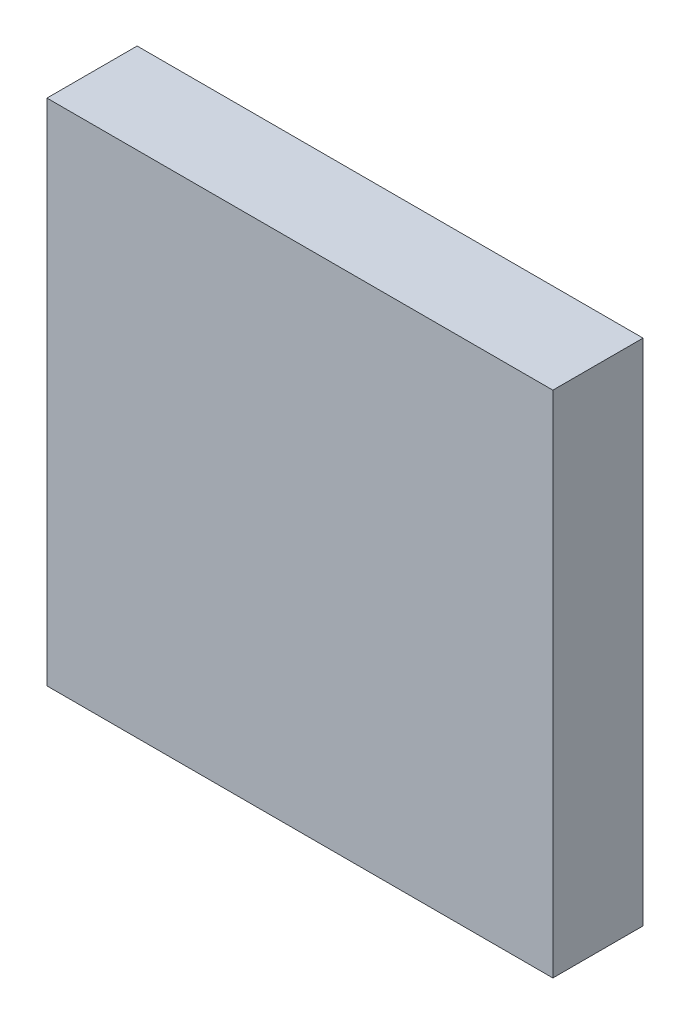
SolidWorks part; units mm, degrees
ref_plane "Front Plane" through (0, 0, 0) normal (0, 0, 1) x (1, 0, 0)
ref_plane "Top Plane" through (0, 0, 0) normal (0, 1, 0) x (1, 0, 0)
ref_plane "Right Plane" through (0, 0, 0) normal (1, 0, 0) x (0, 0, -1)
other "Configuration Table"
sketch "Sketch1" plane through (0, 0, 0) normal (0, 0, 1) x (1, 0, 0)
  line L1 (0, 0) -> (56.1037, 0)
  line L2 (0, 0) -> (0, 56.4588)
  line L3 (0, 56.4588) -> (56.1037, 56.4588)
  line L4 (56.1037, 0) -> (56.1037, 56.4588)
extrude "Boss-Extrude1" add sketch "Sketch1" along normal blind 10
